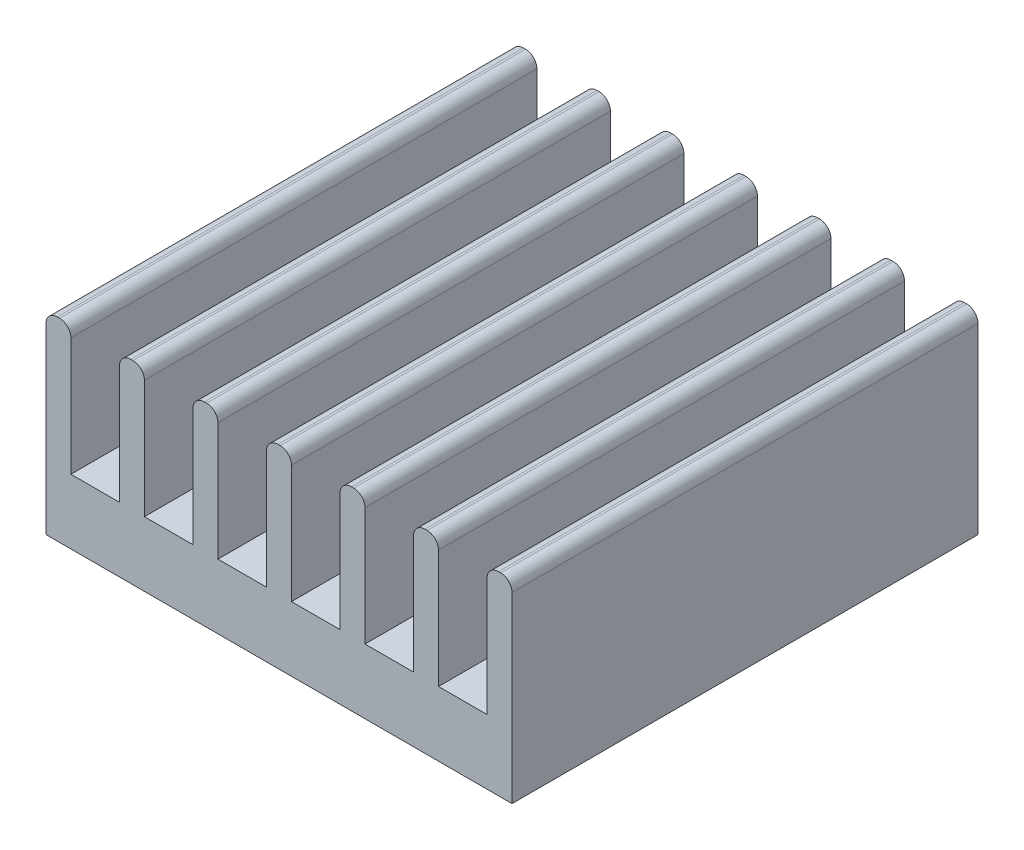
SolidWorks part; units mm, degrees
material "1060 Alloy"
ref_plane "Front Plane" through (0, 0, 0) normal (0, 0, 1) x (1, 0, 0)
ref_plane "Top Plane" through (0, 0, 0) normal (0, 1, 0) x (1, 0, 0)
ref_plane "Right Plane" through (0, 0, 0) normal (1, 0, 0) x (0, 0, -1)
sketch "Sketch1" plane through (0, 0, 0) normal (0, 1, 0) x (1, 0, 0)
  line L1 (0, 0) -> (14.4, 0)
  line L2 (0, 0) -> (0, 14.4)
  line L3 (0, 14.4) -> (14.4, 14.4)
  line L4 (14.4, 0) -> (14.4, 14.4)
  dimension "D1" = 14.4
extrude "Boss-Extrude1" add sketch "Sketch1" against normal blind 2
sketch "Sketch2" plane through (0, 0, 0) normal (0, 0, 1) x (1, 0, 0)
  line L0 (2.2717, 0) -> (2.2717, 4)
  line L1 (0, 0) -> (0.77, 0)
  line L2 (0, 0) -> (0, 4)
  line L3 (0, 4) -> (0.77, 4)
  line L4 (0.77, 0) -> (0.77, 4)
  line L5 (2.2717, 0) -> (3.0417, 0)
  line L6 (3.0417, 0) -> (3.0417, 4)
  line L7 (2.2717, 4) -> (3.0417, 4)
  line L8 (4.5433, 0) -> (4.5433, 4)
  line L9 (4.5433, 0) -> (5.3133, 0)
  line L10 (5.3133, 0) -> (5.3133, 4)
  line L11 (4.5433, 4) -> (5.3133, 4)
  line L12 (6.815, 0) -> (6.815, 4)
  line L13 (6.815, 0) -> (7.585, 0)
  line L14 (7.585, 0) -> (7.585, 4)
  line L15 (6.815, 4) -> (7.585, 4)
  line L16 (9.0867, 0) -> (9.0867, 4)
  line L17 (9.0867, 0) -> (9.8567, 0)
  line L18 (9.8567, 0) -> (9.8567, 4)
  line L19 (9.0867, 4) -> (9.8567, 4)
  line L20 (11.3583, 0) -> (11.3583, 4)
  line L21 (11.3583, 0) -> (12.1283, 0)
  line L22 (12.1283, 0) -> (12.1283, 4)
  line L23 (11.3583, 4) -> (12.1283, 4)
  line L24 (13.63, 0) -> (13.63, 4)
  line L25 (13.63, 0) -> (14.4, 0)
  line L26 (14.4, 0) -> (14.4, 4)
  line L27 (13.63, 4) -> (14.4, 4)
  point P5 (14.4, 0)
  dimension "D1" = 4
  dimension "D2" = 0.77
  dimension "D3" = 7
extrude "Boss-Extrude2" add sketch "Sketch2" against normal up to surface (14.4 mm away) up to face at (7.2, -1, -14.4)
fillet "Fillet1" radius 0.35 14 edges at (14.4, 4, -7.2) (13.63, 4, -7.2) (12.1283, 4, -7.2) (11.3583, 4, -7.2) (9.8567, 4, -7.2) (9.0867, 4, -7.2) (7.585, 4, -7.2) (6.815, 4, -7.2) (5.3133, 4, -7.2) (4.5433, 4, -7.2) (3.0417, 4, -7.2) (2.2717, 4, -7.2) (0.77, 4, -7.2) (0, 4, -7.2)
